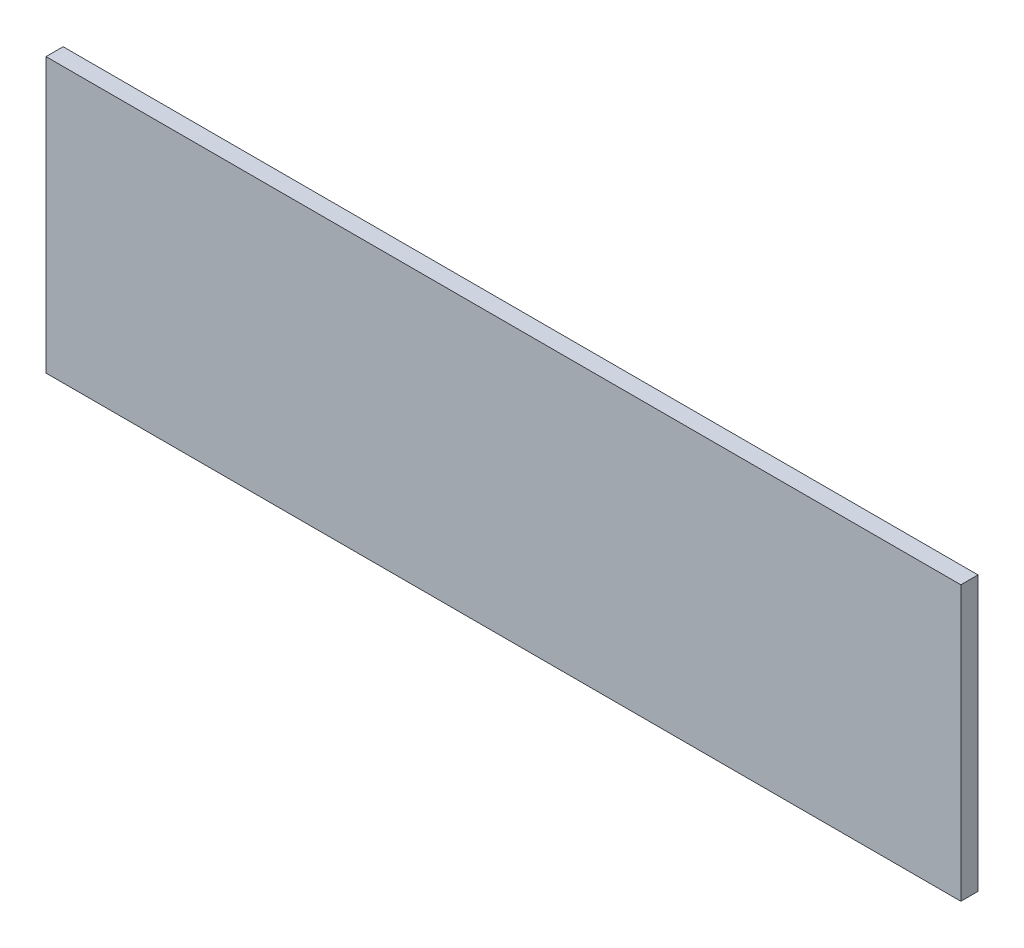
SolidWorks part; units mm, degrees
material "Acrylique (impact moyen-haut)"
ref_plane "Plan de face" through (0, 0, 0) normal (0, 0, 1) x (1, 0, 0)
ref_plane "Plan de dessus" through (0, 0, 0) normal (0, 1, 0) x (1, 0, 0)
ref_plane "Plan de droite" through (0, 0, 0) normal (1, 0, 0) x (0, 0, -1)
sketch "Esquisse1" plane through (0, 0, 0) normal (0, 0, 1) x (1, 0, 0)
  line L1 (-133.5, 40) -> (133.5, 40)
  line L2 (-133.5, 40) -> (-133.5, -40)
  line L3 (-133.5, -40) -> (133.5, -40)
  line L4 (133.5, 40) -> (133.5, -40)
  line L5 (-133.5, 40) -> (133.5, -40) construction
  line L6 (-133.5, -40) -> (133.5, 40) construction
  point P0 (0, 0)
  dimension "D1" = 267
  dimension "D2" = 80
extrude "Boss.-Extru.1" add sketch "Esquisse1" along normal blind 5
sketch "Esquisse2" [suppressed] plane through (0, 0, 5) normal (0, 0, 1) x (1, 0, 0)
  line L1 (-85, 50.5) -> (85, 50.5)
  line L2 (-85, 50.5) -> (-85, -50.5)
  line L3 (-85, -50.5) -> (85, -50.5)
  line L4 (85, 50.5) -> (85, -50.5)
  line L5 (-85, 50.5) -> (85, -50.5) construction
  line L6 (-85, -50.5) -> (85, 50.5) construction
  point P0 (0, 0)
  dimension "D1" = 170
  dimension "D2" = 101
extrude "Enlèv. mat.-Extru.2" [suppressed] cut sketch "Esquisse2" against normal blind 10
